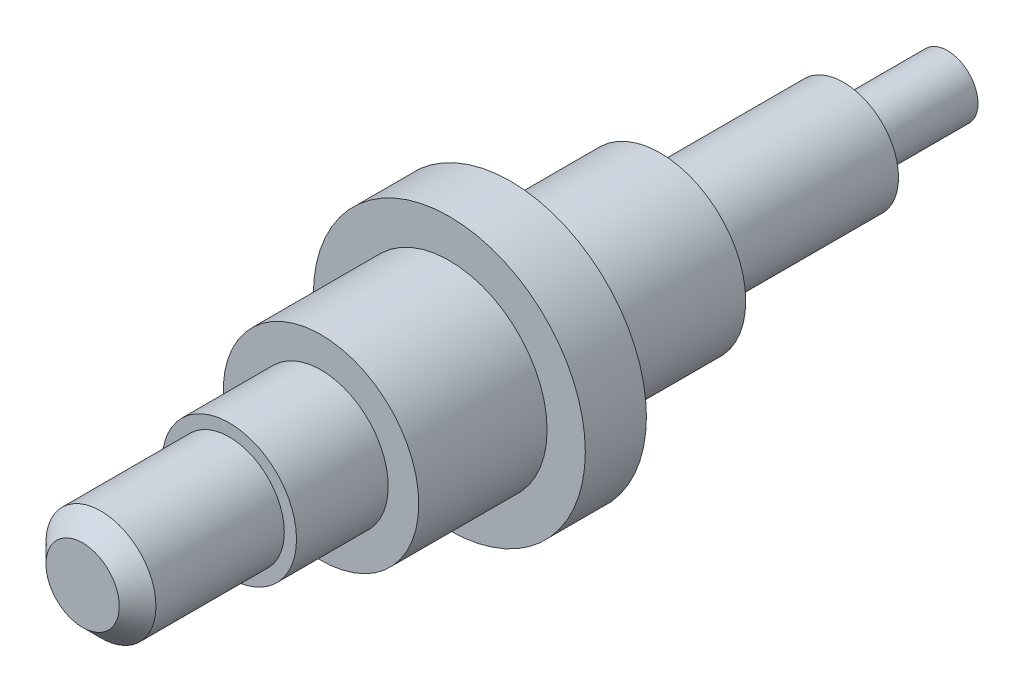
SolidWorks part; units mm, degrees
ref_plane "Front Plane" through (0, 0, 0) normal (0, 0, 1) x (1, 0, 0)
ref_plane "Top Plane" through (0, 0, 0) normal (0, 1, 0) x (1, 0, 0)
ref_plane "Right Plane" through (0, 0, 0) normal (1, 0, 0) x (0, 0, -1)
sketch "Sketch1" plane through (0, 0, 0) normal (1, 0, 0) x (0, 0, -1)
  line L1 (0, 0) -> (24, 0)
  line L2 (0, 0) -> (0, 9)
  line L3 (0, 9) -> (24, 9)
  line L4 (24, 0) -> (24, 9)
  line L5 (24, 0) -> (39, 0)
  line L6 (24, 0) -> (24, 11)
  line L7 (24, 11) -> (39, 11)
  line L8 (39, 0) -> (39, 11)
  line L9 (39, 0) -> (60, 0)
  line L10 (39, 0) -> (39, 16)
  line L11 (39, 16) -> (60, 16)
  line L12 (60, 0) -> (60, 16)
  line L13 (60, 0) -> (70, 0)
  line L14 (60, 0) -> (60, 22.25)
  line L15 (60, 22.25) -> (70, 22.25)
  line L16 (70, 0) -> (70, 22.25)
  line L17 (70, 0) -> (94.5, 0)
  line L18 (70, 0) -> (70, 14)
  line L19 (70, 14) -> (94.5, 14)
  line L20 (94.5, 0) -> (94.5, 14)
  line L21 (94.5, 0) -> (124.5, 0)
  line L22 (94.5, 0) -> (94.5, 9)
  line L23 (94.5, 9) -> (124.5, 9)
  line L24 (124.5, 0) -> (124.5, 9)
  line L25 (124.5, 0) -> (141.5, 0)
  line L26 (124.5, 0) -> (124.5, 5)
  line L27 (124.5, 5) -> (141.5, 5)
  line L28 (141.5, 0) -> (141.5, 5)
  dimension "D1" = 9
  dimension "D2" = 24
  dimension "D3" = 15
  dimension "D4" = 11
  dimension "D5" = 21
  dimension "D6" = 16
  dimension "D7" = 10
  dimension "D8" = 22.25
  dimension "D9" = 14
  dimension "D10" = 30
  dimension "D11" = 9
  dimension "D12" = 17
  dimension "D13" = 5
  dimension "D14" = 24.5
revolve "Revolve1" add sketch "Sketch1" angle 360 about L13
chamfer "Chamfer1" distance 3 angle 45 1 edges at (9, 0, 0)
